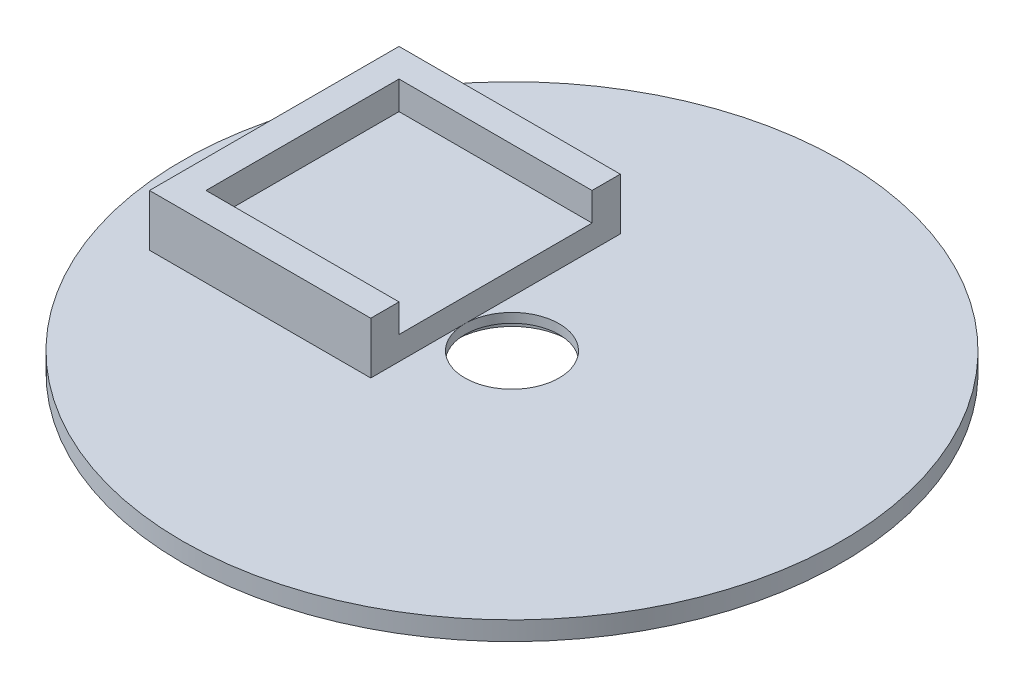
SolidWorks part; units mm, degrees
ref_plane "Front Plane" through (0, 0, 0) normal (0, 0, 1) x (1, 0, 0)
ref_plane "Top Plane" through (0, 0, 0) normal (0, 1, 0) x (1, 0, 0)
ref_plane "Right Plane" through (0, 0, 0) normal (1, 0, 0) x (0, 0, -1)
sketch "Sketch1" plane through (0, 0, 0) normal (0, 1, 0) x (1, 0, 0)
  circle A0 centre (0, 0) radius 35
  dimension "D1" = 70
extrude "Boss-Extrude1" add sketch "Sketch1" along normal blind 2
ref_plane "Plane1" through (0, 0, 0) normal (0, 1, 0) x (1, 0, 0)
sketch "Sketch3" plane through (0, 0, 0) normal (0, 1, 0) x (1, 0, 0)
  circle A0 centre (0, 0) radius 6
  dimension "D1" = 12
extrude "Cut-Extrude2" cut sketch "Sketch3" along normal blind 1
sketch "Sketch4" plane through (0, 0, 0) normal (0, 1, 0) x (1, 0, 0)
  line L0 (0, 0) -> (0, 35) construction
  line L1 (0, 0) -> (-35, 0) construction
  line L2 (-5, 13.5) -> (-5, 16.5)
  line L3 (-5, 13.5) -> (-25.5, 13.5)
  line L5 (-5, -7) -> (-25.5, -7)
  line L6 (-25.5, 13.5) -> (-25.5, -7)
  line L7 (-5, 13.5) -> (-25.5, -7) construction
  line L8 (-5, -7) -> (-25.5, 13.5) construction
  line L9 (-5, 16.5) -> (-28.5, 16.5)
  line L10 (-5, -7) -> (-5, -10)
  line L11 (-5, -10) -> (-28.5, -10)
  line L12 (-28.5, 16.5) -> (-28.5, -10)
  circle A0 centre (0, 0) radius 35 construction
  point P9 (-15.25, 3.25)
  dimension "D1" = 20.5
  dimension "D2" = 20.5
  dimension "D3" = 3
  dimension "D4" = 3
  dimension "D5" = 3
  dimension "D6" = 5
  dimension "D7" = 3.25
extrude "Boss-Extrude2" add sketch "Sketch4" along normal blind 7.5
sketch "Sketch5" plane through (0, 1, 0) normal (0, -1, 0) x (1, 0, 0)
  circle A0 centre (0, 0) radius 5
  dimension "D1" = 10
extrude "Cut-Extrude3" cut sketch "Sketch5" against normal through all both and the other way through all
sketch "Sketch6" plane through (0, 2, 0) normal (0, 1, 0) x (1, 0, 0)
  line L0 (-5, 13.5) -> (-5, 16.5) construction
  line L1 (-5, 16.5) -> (-28.5, 16.5)
  line L2 (-5, 16.5) -> (-5, -10)
  line L3 (-5, -10) -> (-28.5, -10)
  line L4 (-28.5, 16.5) -> (-28.5, -10)
  line L5 (-5, 16.5) -> (-28.5, -10) construction
  line L6 (-5, -10) -> (-28.5, 16.5) construction
  line L7 (-5, 16.5) -> (-5, 13.5) construction
  point P0 (-16.75, 3.25)
extrude "Boss-Extrude3" add sketch "Sketch6" along normal blind 2.5
